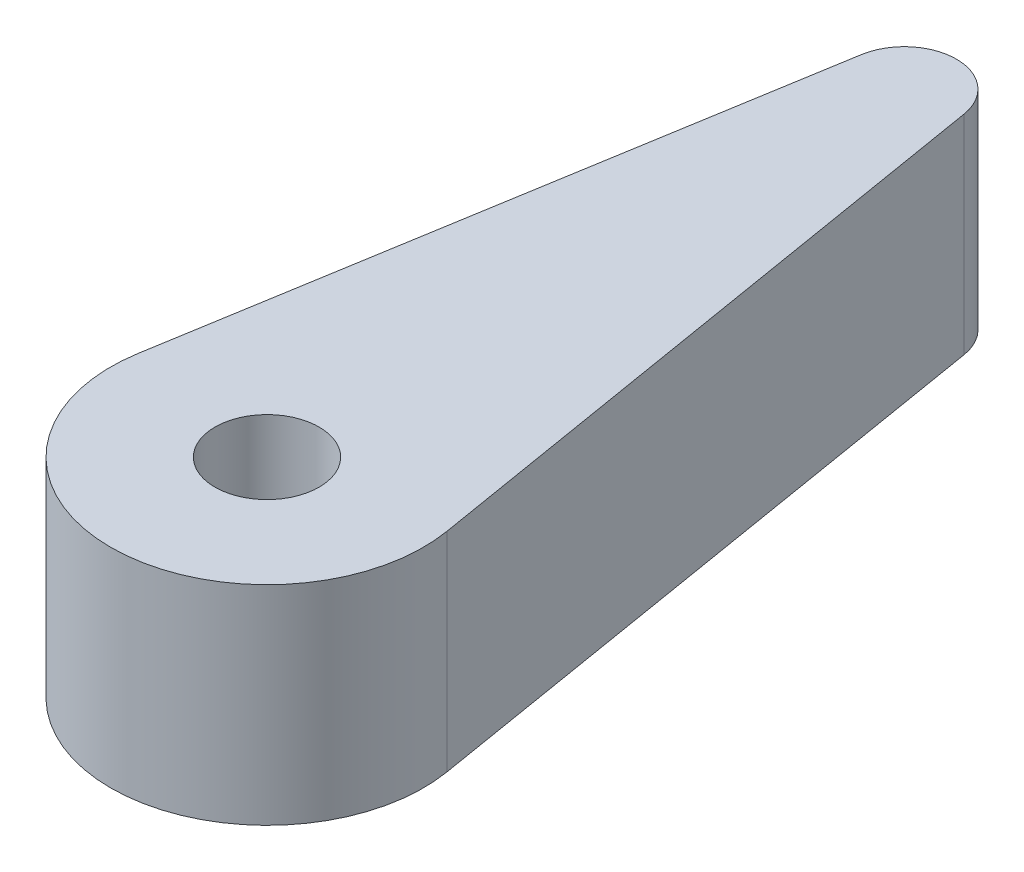
SolidWorks part; units mm, degrees
ref_plane "Front Plane" through (0, 0, 0) normal (0, 0, 1) x (1, 0, 0)
ref_plane "Top Plane" through (0, 0, 0) normal (0, 1, 0) x (1, 0, 0)
ref_plane "Right Plane" through (0, 0, 0) normal (1, 0, 0) x (0, 0, -1)
sketch "Sketch1" plane through (0, 0, 0) normal (0, 1, 0) x (1, 0, 0)
  line L0 (0, 0) -> (0, 30.5773) construction
  line L1 (-7.399, 1.2264) -> (-2.4663, 30.9861)
  line L2 (7.399, 1.2264) -> (2.4679, 30.9769)
  arc A0 (-7.399, 1.2264) -> (7.399, 1.2264) centre (0, 0) ccw
  circle A1 centre (0, 0) radius 2.5
  arc A2 (2.4679, 30.9769) -> (-2.4663, 30.9861) centre (0, 30.5773) ccw
  dimension "D1" = 15
  dimension "D2" = 5
  dimension "D3" = 5
extrude "Boss-Extrude1" add sketch "Sketch1" along normal blind 10
